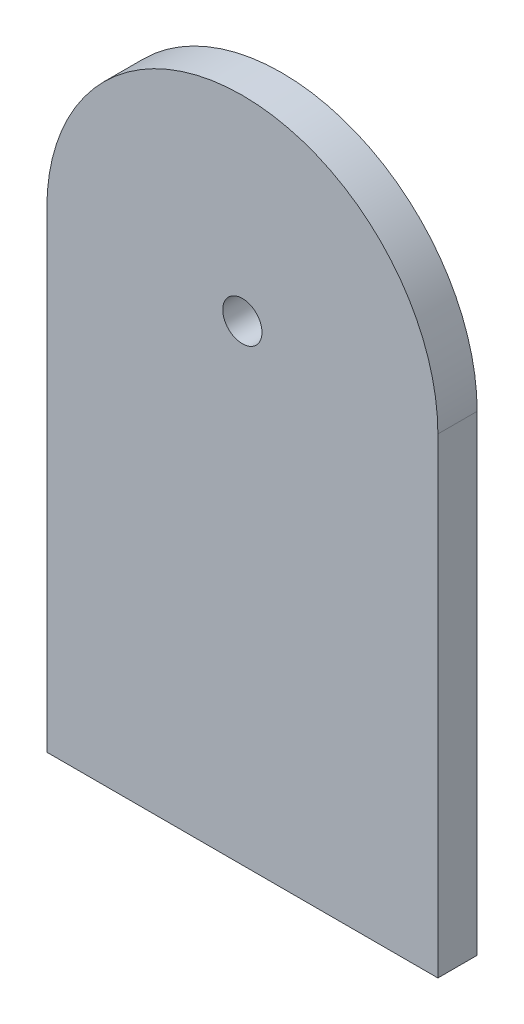
SolidWorks part; units mm, degrees
ref_plane "Front Plane" through (0, 0, 0) normal (0, 0, 1) x (1, 0, 0)
ref_plane "Top Plane" through (0, 0, 0) normal (0, 1, 0) x (1, 0, 0)
ref_plane "Right Plane" through (0, 0, 0) normal (1, 0, 0) x (0, 0, -1)
sketch "Sketch1" plane through (0, 0, 0) normal (0, 0, 1) x (1, 0, 0)
  line L1 (-24.9, 0) -> (24.9, 0)
  line L2 (-24.9, 0) -> (-24.9, 60)
  line L3 (-24.9, 60) -> (24.9, 60)
  line L4 (24.9, 0) -> (24.9, 60)
  circle A0 centre (0, 60) radius 24.9
  dimension "D1" = 49.8
  dimension "D2" = 60
  dimension "D3" = 24.9
  dimension "D4" = 0
ref_point "Point1"
extrude "Boss-Extrude1" add sketch "Sketch1" against normal blind 5 contours L3 A0 | L3 A0 | A0 L2 L1 L4
sketch "Sketch3" plane through (0, 0, 0) normal (0, 0, 1) x (1, 0, 0)
  line L1 (-22, 0) -> (22, 0)
  line L2 (-22, 0) -> (-22, 60)
  line L3 (-22, 60) -> (22, 60)
  line L4 (22, 0) -> (22, 60)
  circle A0 centre (0, 60) radius 22
  dimension "D1" = 60
  dimension "D2" = 44
  dimension "D3" = 22
  dimension "D4" = 0
extrude "Boss-Extrude2" [suppressed] add sketch "Sketch3" against normal blind 20 contours L3 A0 | L3 A0 | A0 L2 L1 L4
sketch "Sketch2" plane through (0, 0, 0) normal (0, 0, 1) x (1, 0, 0)
  circle A0 centre (0, 60) radius 2.5
extrude "Cut-Extrude1" cut sketch "Sketch2" against normal blind 50
sketch "Sketch4" plane through (0, 0, 0) normal (0, 0, 1) x (1, 0, 0)
  line L1 (-22, 0) -> (22, 0)
  line L2 (-22, 0) -> (-22, 60)
  line L3 (-22, 60) -> (22, 60)
  line L4 (22, 0) -> (22, 60)
  circle A0 centre (0, 60) radius 22
  dimension "D1" = 60
  dimension "D2" = 44
